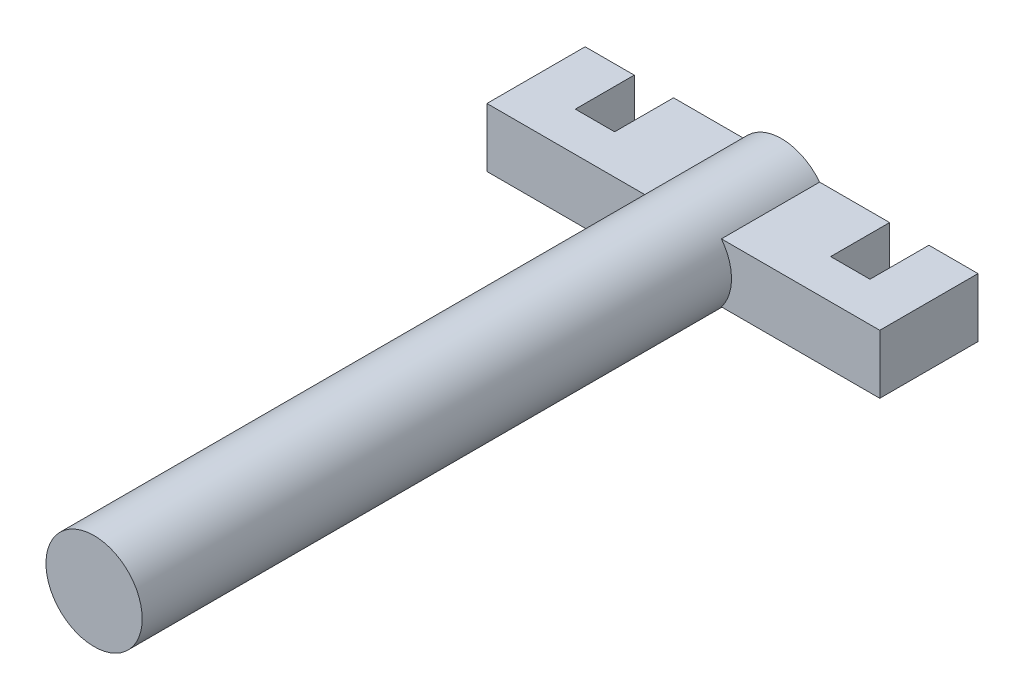
SolidWorks part; units mm, degrees
ref_plane "Front Plane" through (0, 0, 0) normal (0, 0, 1) x (1, 0, 0)
ref_plane "Top Plane" through (0, 0, 0) normal (0, 1, 0) x (1, 0, 0)
ref_plane "Right Plane" through (0, 0, 0) normal (1, 0, 0) x (0, 0, -1)
sketch "Sketch2" plane through (0, 0, 0) normal (0, 0, 1) x (1, 0, 0)
  circle A0 centre (0, 0) radius 2.45
  dimension "D1" = 4.9
extrude "Boss-Extrude1" add sketch "Sketch2" along normal blind 35
sketch "Sketch3" plane through (0, 0, 0) normal (0, 0, -1) x (-1, 0, 0)
  line L0 (-10, 1.5) -> (10, 1.5)
  line L1 (10, 1.5) -> (10, -1.5)
  line L4 (-10, 1.5) -> (-10, -1.5)
  line L5 (-10, -1.5) -> (10, -1.5)
  circle A1 centre (0, 0) radius 2.45 construction
  point P3 (10, 0)
  point P5 (0, 1.5)
  dimension "D1" = 1.5
  dimension "D4" = 20
extrude "Boss-Extrude2" add sketch "Sketch3" against normal blind 5
sketch "Sketch4" plane through (0, 0, 0) normal (0, 0, -1) x (-1, 0, 0)
  line L0 (0, 2.45) -> (0, -2.45) construction
  line L1 (-10, -1.5) -> (-1.9371, -1.5) construction
  line L2 (-7.5, 1.5) -> (-5.5, 1.5)
  line L3 (-7.5, 1.5) -> (-7.5, -1.5)
  line L4 (-7.5, -1.5) -> (-5.5, -1.5)
  line L5 (-5.5, 1.5) -> (-5.5, -1.5)
  line L6 (-7.5, 1.5) -> (-5.5, -1.5) construction
  line L7 (-7.5, -1.5) -> (-5.5, 1.5) construction
  line L8 (-1.9371, 1.5) -> (-10, 1.5) construction
  line L9 (-10, 1.5) -> (-10, -1.5) construction
  line L10 (7.5, -1.5) -> (5.5, 1.5) construction
  line L11 (7.5, 1.5) -> (5.5, -1.5) construction
  line L12 (5.5, 1.5) -> (5.5, -1.5)
  line L13 (7.5, -1.5) -> (5.5, -1.5)
  line L14 (7.5, 1.5) -> (7.5, -1.5)
  line L15 (7.5, 1.5) -> (5.5, 1.5)
  point P8 (-6.5, 0)
  point P23 (6.5, 0)
  dimension "D1" = 2.5
  dimension "D2" = 2
extrude "Cut-Extrude1" cut sketch "Sketch4" against normal offset from surface (3 mm away) 2 up to face at (6.0968, 0, 5)
sketch "Sketch5" plane through (0, 0, 0) normal (0, 1, 0) x (1, 0, 0)
  line L0 (-1.9371, 0) -> (-0.6294, 1.2879)
  line L2 (-0.6294, 1.2879) -> (0.6294, 1.2879)
  line L3 (0.6294, 1.2879) -> (1.9371, 0)
  line L5 (-1.9371, 0) -> (-5.5, 0)
  line L6 (-5.5, 0) -> (-2.1615, 3.2879)
  line L7 (-2.1615, 3.2879) -> (2.1615, 3.2879)
  line L8 (2.1615, 3.2879) -> (5.5, 0)
  line L9 (1.9371, 0) -> (5.5, 0)
  dimension "D2" = 2
  dimension "D3" = 2.5
extrude "Boss-Extrude3" [suppressed] add sketch "Sketch5" along normal up to surface and the other way up to surface
